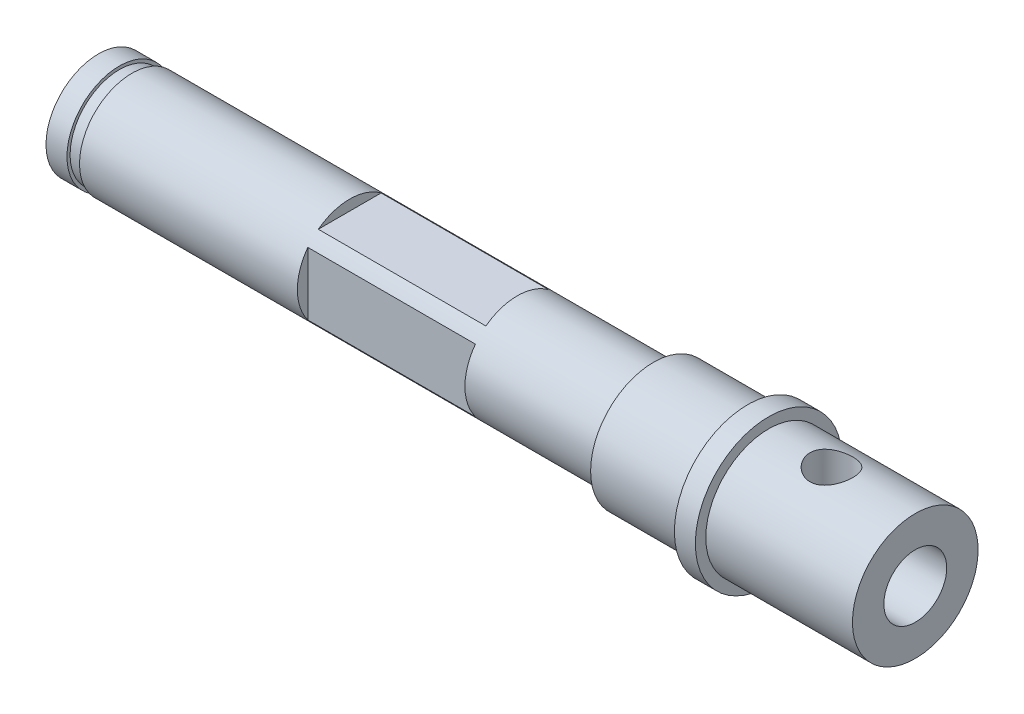
SolidWorks part; units mm, degrees
ref_plane "前视基准面" through (0, 0, 0) normal (0, 0, 1) x (1, 0, 0)
ref_plane "上视基准面" through (0, 0, 0) normal (0, 1, 0) x (1, 0, 0)
ref_plane "右视基准面" through (0, 0, 0) normal (1, 0, 0) x (0, 0, -1)
sketch "草图1" plane through (0, 0, 0) normal (0, 0, 1) x (1, 0, 0)
  line L0 (0, 0) -> (0, 2.5)
  line L1 (0, 2.5) -> (1, 2.5)
  line L2 (1, 2.5) -> (1, 2.35)
  line L3 (1, 2.35) -> (1.6, 2.35)
  line L4 (1.6, 2.35) -> (1.6, 2.5)
  line L5 (1.6, 2.5) -> (26.5, 2.5)
  line L6 (1, 2.5) -> (1.6, 2.5) construction
  line L7 (0, 0) -> (39, 0)
  line L8 (26.5, 2.5) -> (26.5, 3)
  line L9 (26.5, 3) -> (31, 3)
  line L10 (31, 3) -> (31, 3.5)
  line L11 (31, 3.5) -> (32, 3.5)
  line L12 (32, 3.5) -> (32, 3)
  line L13 (32, 3) -> (39, 3)
  line L14 (39, 3) -> (39, 0)
  dimension "D1" = 3
  dimension "D2" = 2.5
  dimension "D3" = 1
  dimension "D4" = 4.5
  dimension "D5" = 29.4
  dimension "D6" = 0.6
  dimension "D7" = 2.35
  dimension "D8" = 1
  dimension "D9" = 3.5
  dimension "D10" = 3
  dimension "D11" = 7
revolve "旋转1" add sketch "草图1" angle 360 about L7
ref_plane "基准面1" through (0, 0, 2.5) normal (0, 0, 1) x (1, 0, 0)
sketch "草图2" plane through (0, 0, 2.5) normal (0, 0, 1) x (1, 0, 0)
  line L0 (1.6, -2.5) -> (26.5, -2.5) construction
  line L1 (12, -2.5) -> (20, -2.5)
  line L2 (12, -2.5) -> (12, 2.5)
  line L3 (12, 2.5) -> (20, 2.5)
  line L4 (20, -2.5) -> (20, 2.5)
  line L5 (26.5, 2.5) -> (1.6, 2.5) construction
  line L6 (0, 0) -> (20, 0) construction
  dimension "D1" = 8
  dimension "D2" = 20
extrude "切除-拉伸1" cut sketch "草图2" against normal blind 0.5
ref_plane "基准面2" through (0, 2.5, 0) normal (0, 1, 0) x (1, 0, 0)
sketch "草图3" plane through (0, 2.5, 0) normal (0, 1, 0) x (1, 0, 0)
  line L0 (26.5, 2.5) -> (1.6, 2.5) construction
  line L1 (12, -2.5) -> (20, -2.5)
  line L2 (12, -2.5) -> (12, 2.5)
  line L3 (12, 2.5) -> (20, 2.5)
  line L4 (20, -2.5) -> (20, 2.5)
extrude "切除-拉伸2" cut sketch "草图3" against normal blind 0.5
sketch "草图4" plane through (39, 0, 0) normal (1, 0, 0) x (0, 0, -1)
  circle A0 centre (0, 0) radius 1.5
  dimension "D1" = 3
hole_wizard "大小mm 暗销孔1" positions "3D草图1" profile "草图5" hole size "Ø3.0" standard "GB"
sketch3d "3D草图1"
  point P0 (39, 0, 0)
sketch "草图5" plane through (39, 0, 0) normal (0, 1, 0) x (0, 0, -1)
  line L0 (0, 0) -> (0, 10.9013)
  line L1 (0, 10.9013) -> (1.5, 10)
  line L2 (1.5, 10) -> (1.5, 0)
  line L5 (1.5, 0) -> (0, 0)
  line L10 (0, 10.9013) -> (-1.5, 10) construction
  line L11 (0, -6.35) -> (0, 107.95) construction
  dimension "孔直径" = 3
  dimension "孔深度" = 10
  dimension "导头角度" = 118
ref_plane "基准面3" through (0, 3, 0) normal (0, 1, 0) x (1, 0, 0)
sketch "草图6" plane through (0, 3, 0) normal (0, 1, 0) x (1, 0, 0)
  line L0 (39, 0) -> (35, 0) construction
  line L1 (39, -3) -> (39, 3) construction
  dimension "D1" = 4
hole_wizard "M2.5 螺纹孔1" positions "3D草图2" profile "草图7" tap size "M2.5" standard "GB"
sketch3d "3D草图2"
  point P4 (35, 3, 0)
sketch "草图7" plane through (35, 3, 0) normal (1, 0, 0) x (0, 0, 1)
  line L0 (0, 0) -> (0, 3.6159)
  line L1 (0, 3.6159) -> (1.025, 3)
  line L2 (1.025, 3) -> (1.025, 0)
  line L5 (1.025, 0) -> (0, 0)
  line L10 (0, 3.6159) -> (-1.025, 3) construction
  line L11 (0, -6.35) -> (0, 107.95) construction
  dimension "螺纹孔钻头直径" = 2.05
  dimension "螺纹孔钻头深度" = 3
  dimension "导头角度" = 118
cosmetic thread "孔螺蚊线1" parameters "D1"=1.9048, "D2"=2.5
